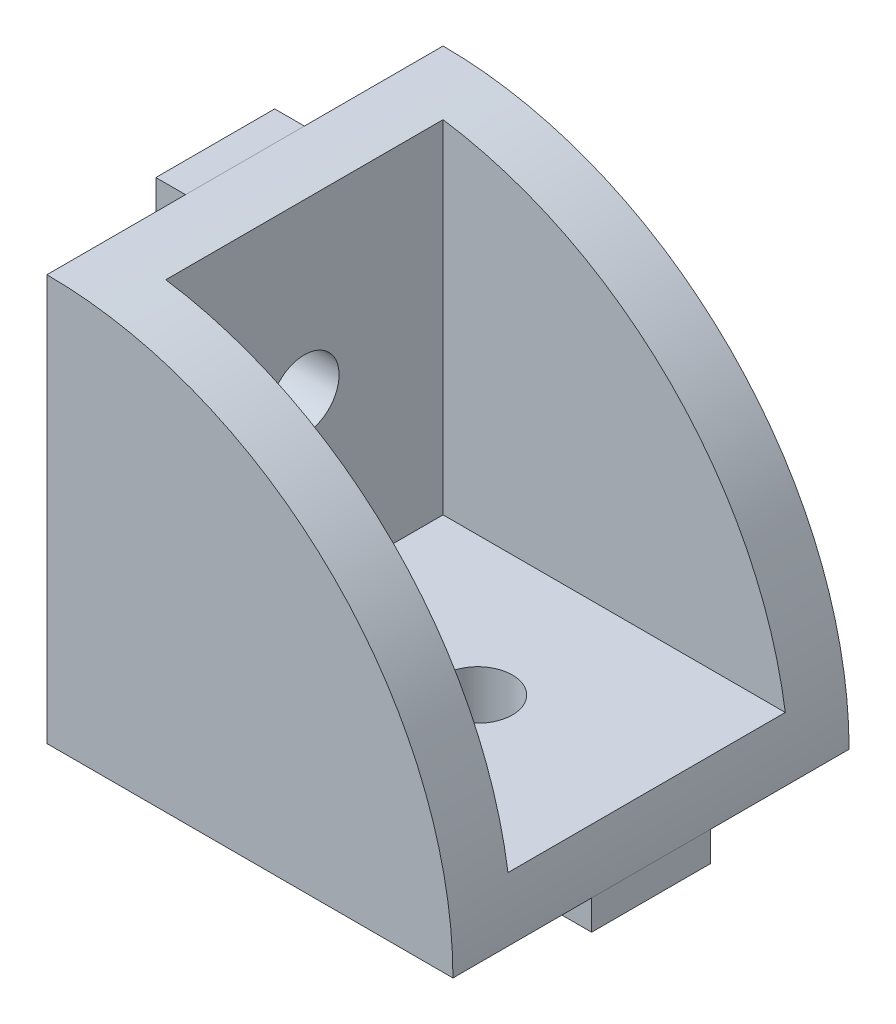
SolidWorks part; units mm, degrees
ref_plane "Ön Düzlem" through (0, 0, 0) normal (0, 0, 1) x (1, 0, 0)
ref_plane "Üst Düzlem" through (0, 0, 0) normal (0, 1, 0) x (1, 0, 0)
ref_plane "Sağ Düzlem" through (0, 0, 0) normal (1, 0, 0) x (0, 0, -1)
sketch "Çizim1" plane through (0, 0, 0) normal (0, 0, 1) x (1, 0, 0)
  line L0 (0, 20.5) -> (0, 0)
  line L1 (0, 0) -> (20.5, 0)
  arc A0 (20.5, 0) -> (0, 20.5) centre (0, 0) ccw
  dimension "D1" = 20.5
  dimension "D2" = 20.5
extrude "Yükseklik-Ekstrüzyon1" add sketch "Çizim1" along normal blind 20
sketch "Çizim2" plane through (0, 0, 0) normal (1, 0, 0) x (0, 0, -1)
  line L0 (-20, 20.5) -> (0, 20.5) construction
  line L1 (-17, 3) -> (-3, 3)
  line L2 (-17, 3) -> (-17, 20.5)
  line L3 (-17, 20.5) -> (-3, 20.5)
  line L4 (-3, 3) -> (-3, 20.5)
  line L5 (-20, 20.5) -> (-20, 0) construction
  line L6 (0, 0) -> (0, 20.5) construction
  line L7 (-20, 0) -> (0, 0) construction
  dimension "D1" = 3
  dimension "D2" = 3
  dimension "D3" = 3
extrude "Kes-Ekstrüzyon1" cut sketch "Çizim2" along normal through all from offset 3
sketch "Çizim6" plane through (3, 0, 0) normal (1, 0, 0) x (0, 0, -1)
  line L0 (-20, 0) -> (0, 0) construction
  line L1 (-13, 0) -> (-7, 0)
  line L2 (-13, 0) -> (-13, -1.5)
  line L3 (-13, -1.5) -> (-7, -1.5)
  line L4 (-7, 0) -> (-7, -1.5)
  line L5 (-10, -1.5) -> (-10, 3) construction
  line L6 (-17, 3) -> (-3, 3) construction
  dimension "D1" = 6
  dimension "D2" = 1.5
extrude "Yükseklik-Ekstrüzyon3" add sketch "Çizim6" along normal through all
sketch "Эскиз2" plane through (0, -1.5, 0) normal (0, -1, 0) x (1, 0, 0)
  line L0 (20.5, 10) -> (3, 10) construction
  line L1 (20.5, 13) -> (20.5, 7) construction
  line L2 (3, 13) -> (3, 7) construction
  circle A0 centre (11.75, 10) radius 1.75
  dimension "D1" = 3.5
extrude "Вырез-Вытянуть2" cut sketch "Эскиз2" against normal blind 5
sketch "Эскиз3" plane through (0, 0, 0) normal (-1, 0, 0) x (0, 0, 1)
  line L0 (20, 20.5) -> (0, 20.5) construction
  line L1 (13, 20.5) -> (7, 20.5)
  line L2 (13, 20.5) -> (13, 3)
  line L3 (13, 3) -> (7, 3)
  line L4 (7, 20.5) -> (7, 3)
  line L5 (13, 0) -> (13, -1.5) construction
  dimension "D1" = 0
  dimension "D2" = 6
  dimension "D3" = 17.5
extrude "Бобышка-Вытянуть1" add sketch "Эскиз3" along normal blind 1.5
sketch "Эскиз4" plane through (-1.5, 0, 0) normal (-1, 0, 0) x (0, 0, 1)
  line L0 (7, 20.5) -> (7, 3) construction
  line L1 (13, 20.5) -> (7, 20.5) construction
  circle A0 centre (10, 11.75) radius 1.75
  point P6 (10, 20.5)
  dimension "D1" = 3.5
  dimension "D2" = 3
  dimension "D3" = 8.75
extrude "Вырез-Вытянуть3" cut sketch "Эскиз4" against normal blind 5
